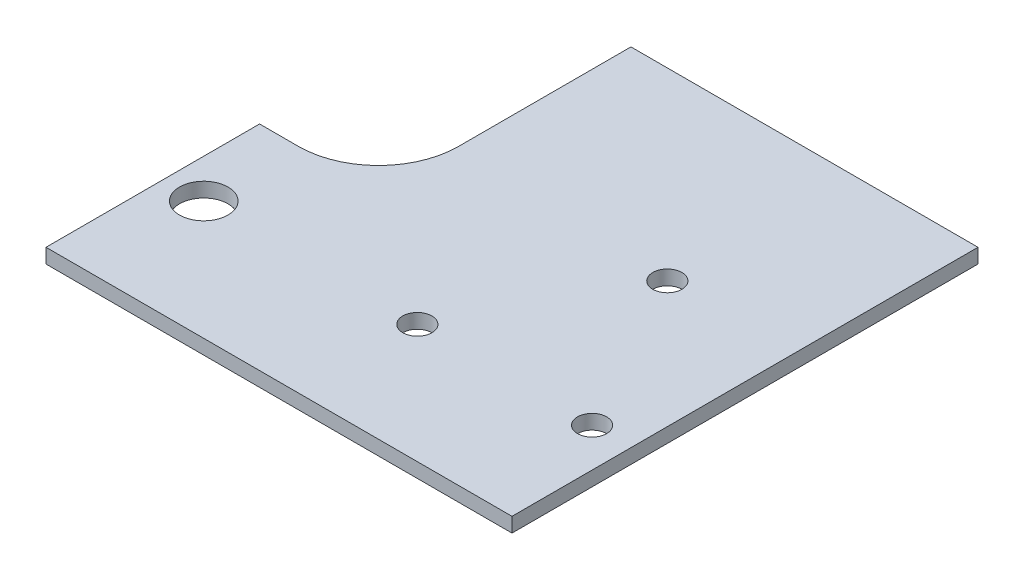
SolidWorks part; units mm, degrees
material "Malleable Cast Iron"
ref_plane "Front Plane" through (0, 0, 0) normal (0, 0, 1) x (1, 0, 0)
ref_plane "Top Plane" through (0, 0, 0) normal (0, 1, 0) x (1, 0, 0)
ref_plane "Right Plane" through (0, 0, 0) normal (1, 0, 0) x (0, 0, -1)
sketch "Sketch1" plane through (0, 0, 0) normal (0, 1, 0) x (1, 0, 0)
  line L0 (-304.8, 304.8) -> (304.8, -304.8) construction
  line L1 (-304.8, 304.8) -> (304.8, 304.8)
  line L2 (-304.8, 304.8) -> (-304.8, -304.8)
  line L3 (-304.8, -304.8) -> (304.8, -304.8)
  line L4 (304.8, 304.8) -> (304.8, -304.8)
  dimension "D1" = 609.6
  dimension "D2" = 609.6
extrude "Boss-Extrude1" add sketch "Sketch1" along normal blind 19.05
sketch "Sketch8" plane through (0, 19.05, 0) normal (0, 1, 0) x (-1, 0, 0)
  line L0 (304.8, 304.8) -> (-304.8, 304.8) construction
  line L1 (-304.8, 304.8) -> (-304.8, -304.8) construction
  circle A0 centre (-292.1, 292.1) radius 3.175
  dimension "D1" = 6.35
  dimension "D2" = 12.7
  dimension "D3" = 12.7
extrude "Cut-Extrude5" [suppressed] cut sketch "Sketch8" against normal through all
pattern_linear "LPattern1" [suppressed] count 24 spacing 25.4 count 24 spacing 25.4
sketch "Sketch2" plane through (0, 0, 0) normal (0, -1, 0) x (1, 0, 0)
  circle A0 centre (-254, 149.225) radius 31.75
  dimension "D1" = 63.5
extrude "Cut-Extrude1" cut sketch "Sketch2" against normal through all
sketch "Sketch9" plane through (0, 0, 0) normal (0, -1, 0) x (1, 0, 0)
  circle A0 centre (-254, -79.375) radius 104.775
  circle A1 centre (-254, -79.375) radius 101.6 construction
  dimension "D1" = 209.55
extrude "Cut-Extrude8" cut sketch "Sketch9" against normal through all
sketch "Sketch10" plane through (0, 0, 0) normal (0, -1, 0) x (1, 0, 0)
  line L0 (-254, -79.375) -> (-149.225, -79.375)
  line L1 (-149.225, -79.375) -> (-149.225, -304.8)
  line L2 (304.8, -304.8) -> (-304.8, -304.8) construction
  line L3 (-149.225, -304.8) -> (-304.8, -304.8)
  line L4 (-304.8, -304.8) -> (-304.8, -79.375)
  line L5 (-304.8, -79.375) -> (-254, -79.375)
  arc A0 (-304.8, -171.011) -> (-304.8, 12.261) centre (-254, -79.375) ccw construction
  point P0 (-254, -79.375)
extrude "Cut-Extrude9" cut sketch "Sketch10" against normal through all
sketch "Sketch11" plane through (0, 0, 0) normal (0, -1, 0) x (1, 0, 0)
  line L0 (-254, -79.375) -> (-254, 25.4)
  line L1 (-254, 25.4) -> (-377.072, 25.4)
  line L2 (-377.072, 25.4) -> (-377.072, -79.375)
  line L3 (-377.072, -79.375) -> (-254, -79.375)
  arc A0 (-149.225, -79.375) -> (-304.8, 12.261) centre (-254, -79.375) ccw construction
  point P0 (-254, -79.375)
extrude "Cut-Extrude10" cut sketch "Sketch11" against normal through all
sketch "Sketch12" plane through (0, 0, 0) normal (0, -1, 0) x (1, 0, 0)
  circle A0 centre (25.4, 149.225) radius 19.05
  circle A1 centre (254, 149.225) radius 19.05
  circle A2 centre (25.4, 149.225) radius 19.05 construction
  circle A3 centre (254, 149.225) radius 19.05 construction
extrude "Cut-Extrude11" cut sketch "Sketch12" against normal through all
sketch "Sketch13" plane through (0, 0, 0) normal (0, -1, 0) x (1, 0, 0)
  line L0 (304.8, 304.8) -> (304.8, -304.8) construction
  line L1 (304.8, -304.8) -> (-149.225, -304.8) construction
  circle A0 centre (139.7, -63.5) radius 19.05
  dimension "D1" = 38.1
  dimension "D2" = 165.1
  dimension "D3" = 241.3
extrude "Cut-Extrude12" cut sketch "Sketch13" against normal through all
